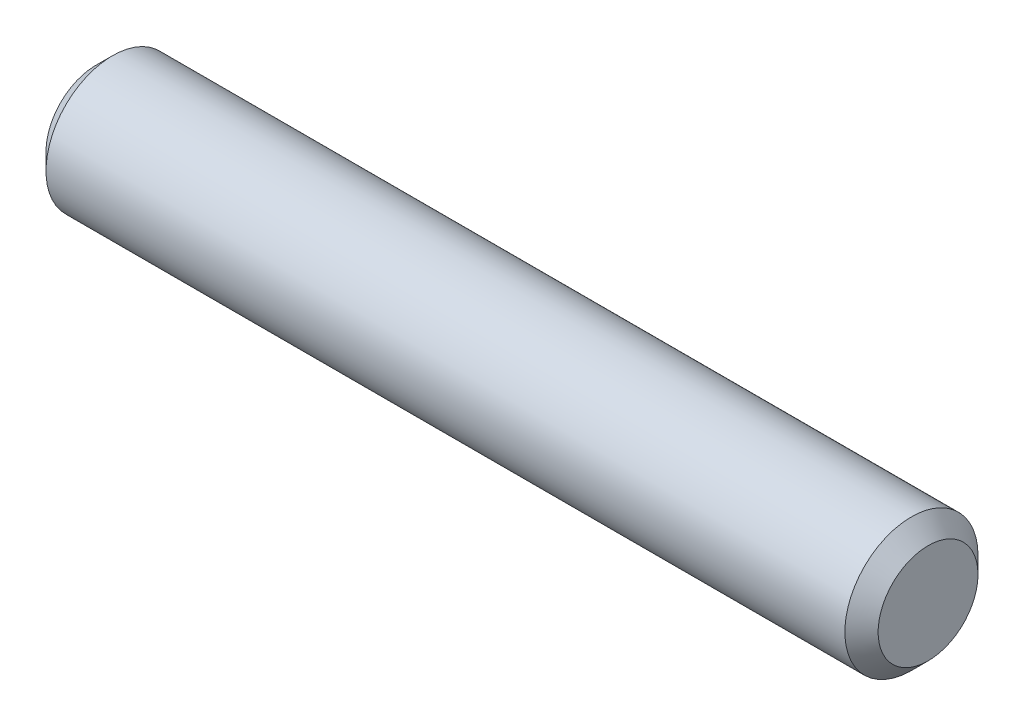
SolidWorks part; units mm, degrees
ref_plane "Piano frontale" through (0, 0, 0) normal (0, 0, 1) x (1, 0, 0)
ref_plane "Piano superiore" through (0, 0, 0) normal (0, 1, 0) x (1, 0, 0)
ref_plane "Piano destro" through (0, 0, 0) normal (1, 0, 0) x (0, 0, -1)
sketch "Schizzo1" [suppressed] plane through (0, 0, 0) normal (1, 0, 0) x (0, 0, -1)
  circle A0 centre (0, 0) radius 4
  dimension "D1" = 8
extrude "Estrusione-Estrusione1" [suppressed] add sketch "Schizzo1" along normal blind 30
chamfer "Smusso1" [suppressed] distance 1 angle 45
sketch "Schizzo2" plane through (0, 0, 0) normal (1, 0, 0) x (0, 0, -1)
  circle A0 centre (0, 0) radius 4
  dimension "D1" = 8
extrude "Estrusione-Estrusione2" add sketch "Schizzo2" along normal blind 50
chamfer "Smusso2" distance 1 angle 45 2 edges at (0, 0, -4) (50, 0, -4)
